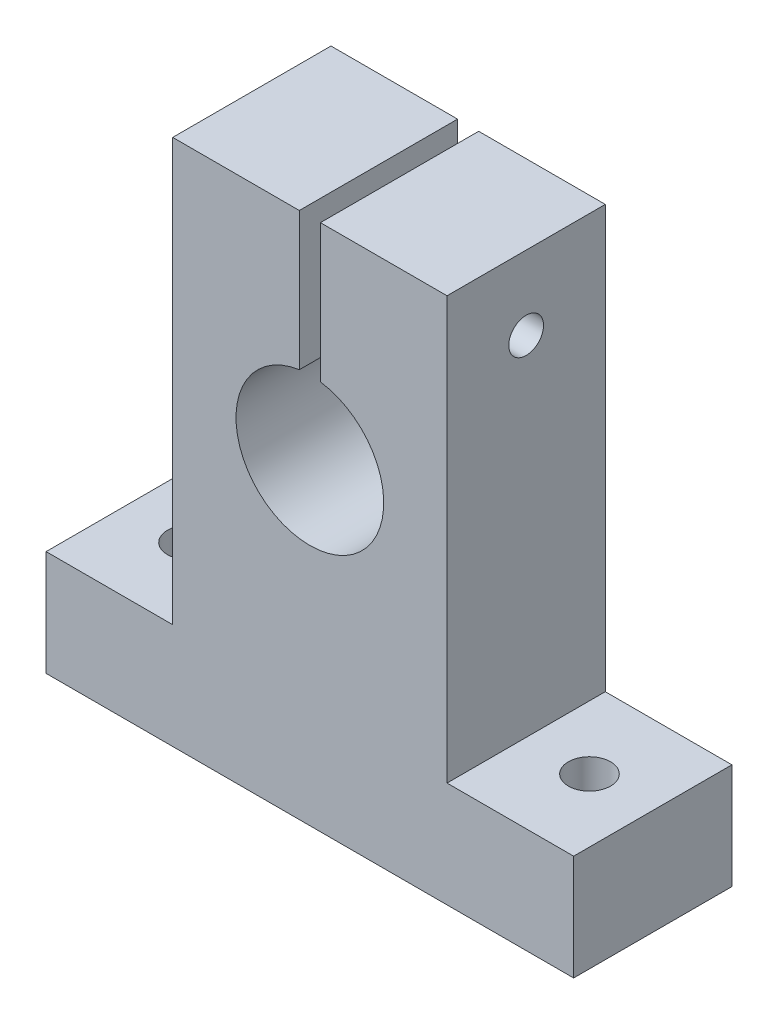
SolidWorks part; units mm, degrees
ref_plane "Front Plane" through (0, 0, 0) normal (0, 0, 1) x (1, 0, 0)
ref_plane "Top Plane" through (0, 0, 0) normal (0, 1, 0) x (1, 0, 0)
ref_plane "Right Plane" through (0, 0, 0) normal (1, 0, 0) x (0, 0, -1)
sketch "Sketch1" plane through (0, 0, 0) normal (0, 0, 1) x (1, 0, 0)
  line L1 (-26, 0) -> (-26, -40)
  line L2 (-26, -40) -> (-38, -40)
  line L3 (-38, -40) -> (-38, -50)
  line L4 (-38, -50) -> (12, -50)
  line L5 (12, -50) -> (12, -40)
  line L6 (12, -40) -> (0, -40)
  line L7 (0, -40) -> (0, 0)
  line L8 (-14, 0) -> (-14, -13.0718)
  line L9 (-12, 0) -> (-12, -13.0718)
  line L10 (-26, 0) -> (-14, 0)
  line L11 (-12, 0) -> (0, 0)
  arc A7 (-14, -13.0718) -> (-12, -13.0718) centre (-13, -20) ccw
  point P11 (0, -40)
  point P14 (-26, -40)
  point P17 (12, -40)
  point P20 (-38, -40)
  point P23 (0, 0)
  dimension "D6" = 13
  dimension "D7" = 7
  dimension "D9" = 1
  dimension "D14" = 0
  dimension "D1" = 50
  dimension "D2" = 12
  dimension "D3" = 12
  dimension "D4" = 10
  dimension "D5" = 50
  dimension "D8" = 2
  dimension "D11" = 30
  dimension "D13" = 50
extrude "Boss-Extrude1" add sketch "Sketch1" along normal blind 15
sketch "Sketch5" plane through (0, -40, 0) normal (0, 1, 0) x (1, 0, 0)
  line L0 (12, 0) -> (0, 0) construction
  line L1 (-26, 0) -> (-38, 0) construction
  line L4 (12, -15) -> (12, 0) construction
  line L5 (-38, -15) -> (-38, 0) construction
  circle A0 centre (6, -7.5) radius 2
  circle A1 centre (-32, -7.5) radius 2
  dimension "D3" = 4
  dimension "D4" = 4
  dimension "D1" = 7.5
  dimension "D2" = 7.5
  dimension "D5" = 6
  dimension "D6" = 6
extrude "Cut-Extrude3" cut sketch "Sketch5" against normal blind 15
hole_wizard "Dégagement M41" positions "Esquisse1" profile "Esquisse2" hole size "M4" standard "ISO"
sketch "Esquisse1" plane through (-26, 0, 0) normal (-1, 0, 0) x (0, 0, 1)
  line L0 (15, 0) -> (0, 0) construction
  point P0 (7.5699, -7)
  dimension "D1" = 7
sketch "Esquisse2" plane through (-26, -7, 7.5699) normal (0, 1, 0) x (0, 0, 1)
  line L0 (0, 0) -> (0, 12)
  line L1 (0, 12) -> (2.25, 12)
  line L2 (2.25, 12) -> (2.25, 0)
  line L5 (2.25, 0) -> (0, 0)
  line L11 (0, -6.35) -> (0, 107.95) construction
  dimension "Diamètre du perçage jusqu'au prochain" = 4.5
  dimension "Profondeur du perçage jusqu'au prochain" = 12
hole_wizard "Trou taraudé M41" positions "Esquisse3" profile "Esquisse4" tap size "M4" standard "ISO" end condition up to next
sketch "Esquisse3" plane through (0, 0, 0) normal (1, 0, 0) x (0, 0, -1)
  line L0 (-15, -40) -> (-15, 0) construction
  line L1 (-15, 0) -> (0, 0) construction
  point P0 (-7.5, -7)
  dimension "D1" = 7.5
  dimension "D2" = 7
sketch "Esquisse4" plane through (0, -7, 7.5) normal (0, 1, 0) x (0, 0, -1)
  line L0 (0, 0) -> (0, 12)
  line L1 (0, 12) -> (1.65, 12)
  line L2 (1.65, 12) -> (1.65, 0)
  line L5 (1.65, 0) -> (0, 0)
  line L11 (0, -6.35) -> (0, 107.95) construction
  dimension "Diamètre du trou pour taraudage jusqu'au prochain" = 3.3
  dimension "Profondeur du trou pour taraudage jusqu'au prochain" = 12
cosmetic thread "Filetage de perçage1" parameters "D2"=4
